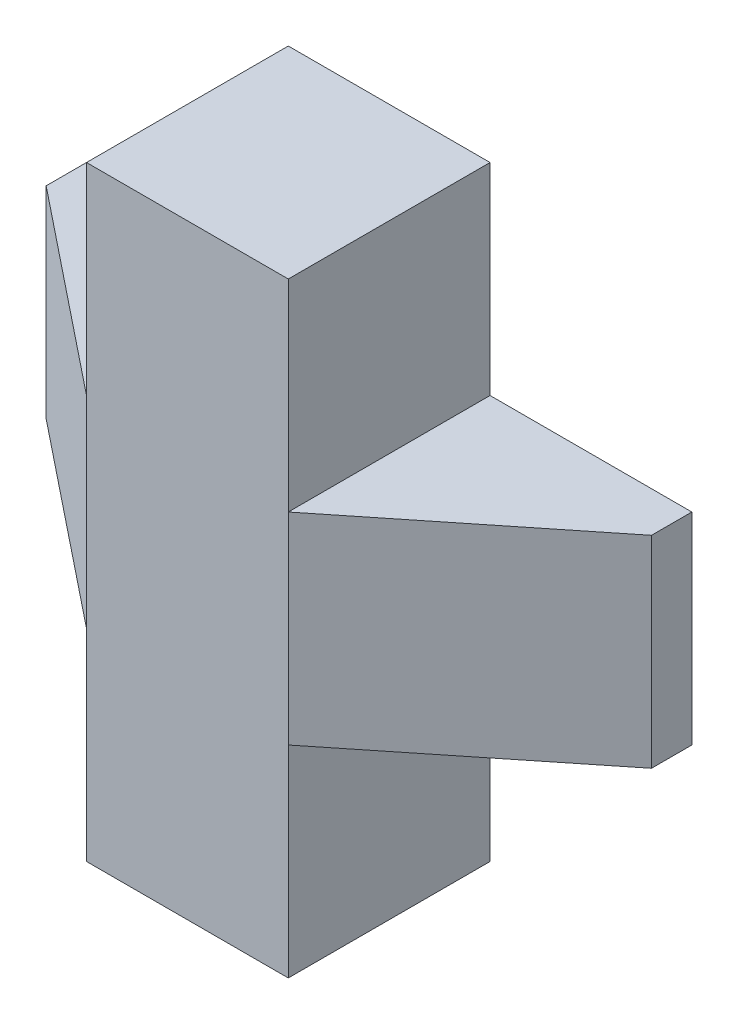
SolidWorks part; units mm, degrees
ref_plane "Front Plane" through (0, 0, 0) normal (0, 0, 1) x (1, 0, 0)
ref_plane "Top Plane" through (0, 0, 0) normal (0, 1, 0) x (1, 0, 0)
ref_plane "Right Plane" through (0, 0, 0) normal (1, 0, 0) x (0, 0, -1)
sketch "Sketch1" plane through (0, 0, 0) normal (0, 0, 1) x (1, 0, 0)
  line L1 (75, -75) -> (-75, -75)
  line L2 (75, -75) -> (75, 75)
  line L3 (75, 75) -> (-75, 75)
  line L4 (-75, -75) -> (-75, 75)
  line L5 (75, -75) -> (-75, 75) construction
  line L6 (75, 75) -> (-75, -75) construction
  point P0 (0, 0)
  dimension "D1" = 150
  dimension "D2" = 150
extrude "Boss-Extrude1" add sketch "Sketch1" along normal blind 50
sketch "Sketch2" plane through (0, 0, 50) normal (0, 0, 1) x (1, 0, 0)
  line L2 (-75, 75) -> (-25, 75)
  line L3 (-75, 75) -> (-75, 25)
  line L4 (-75, 25) -> (-25, 25)
  line L5 (-25, 75) -> (-25, 25)
  line L6 (75, 75) -> (25, 75)
  line L7 (75, 75) -> (75, 25)
  line L8 (75, 25) -> (25, 25)
  line L9 (25, 75) -> (25, 25)
  line L10 (75, -75) -> (25, -75)
  line L11 (75, -75) -> (75, -25)
  line L12 (75, -25) -> (25, -25)
  line L13 (25, -75) -> (25, -25)
  line L14 (-75, -75) -> (-25, -75)
  line L15 (-75, -75) -> (-75, -25)
  line L16 (-75, -25) -> (-25, -25)
  line L17 (-25, -75) -> (-25, -25)
  dimension "D1" = 50
extrude "Cut-Extrude1" cut sketch "Sketch2" against normal blind 50
sketch "Sketch3" plane through (0, 25, 0) normal (0, 1, 0) x (1, 0, 0)
  line L0 (25, -50) -> (75, -10)
  line L1 (75, 0) -> (75, -50) construction
  line L2 (75, -10) -> (75, -50)
  line L3 (75, -50) -> (25, -50)
  line L4 (0, -27.5) -> (0, 27.5) construction
  line L5 (-75, -10) -> (-75, -50)
  line L6 (-25, -50) -> (-75, -10)
  line L7 (-75, -50) -> (-25, -50)
  dimension "D1" = 10
extrude "Cut-Extrude2" cut sketch "Sketch3" against normal blind 50
